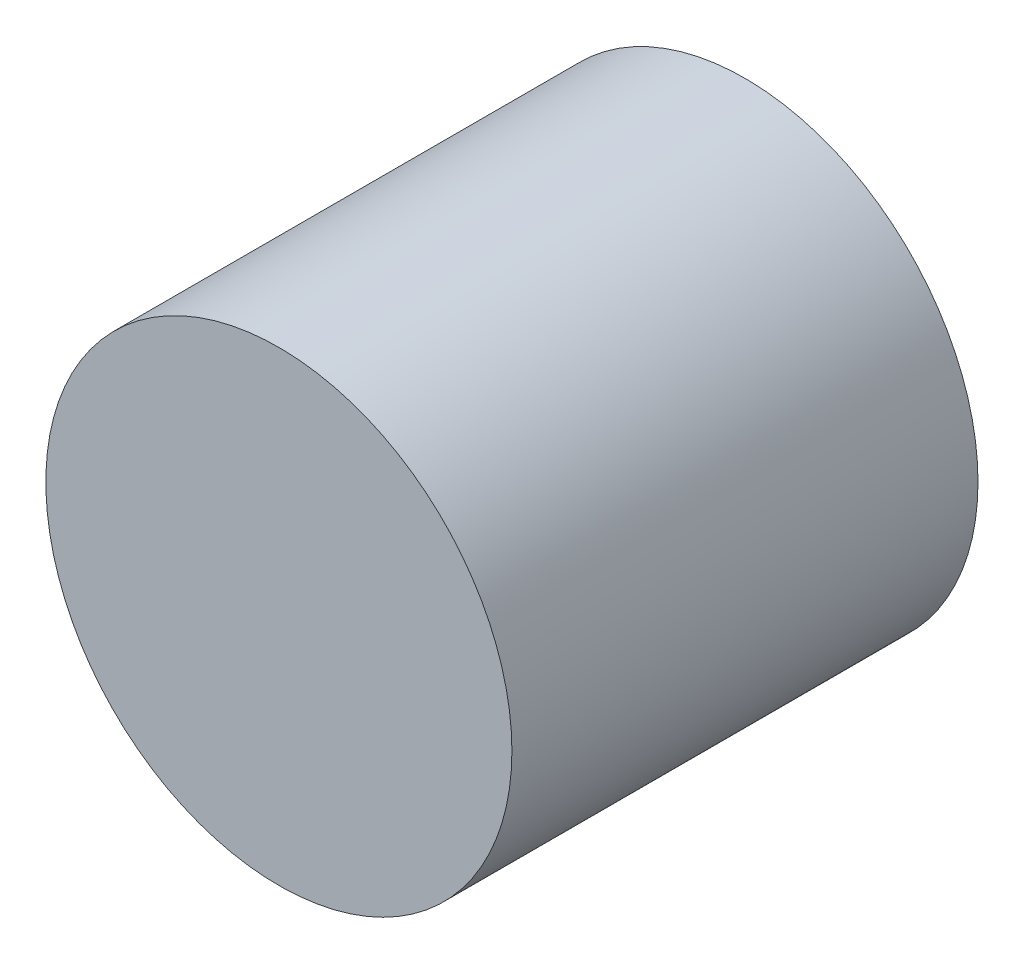
SolidWorks part; units mm, degrees
ref_plane "Front Plane" through (0, 0, 0) normal (0, 0, 1) x (1, 0, 0)
ref_plane "Top Plane" through (0, 0, 0) normal (0, 1, 0) x (1, 0, 0)
ref_plane "Right Plane" through (0, 0, 0) normal (1, 0, 0) x (0, 0, -1)
sketch "Sketch3" plane through (0, 0, 0) normal (0, 0, 1) x (1, 0, 0)
  circle A0 centre (0, 0) radius 125
  dimension "D1" = 250
extrude "Boss-Extrude1" add sketch "Sketch3" along normal blind 250
